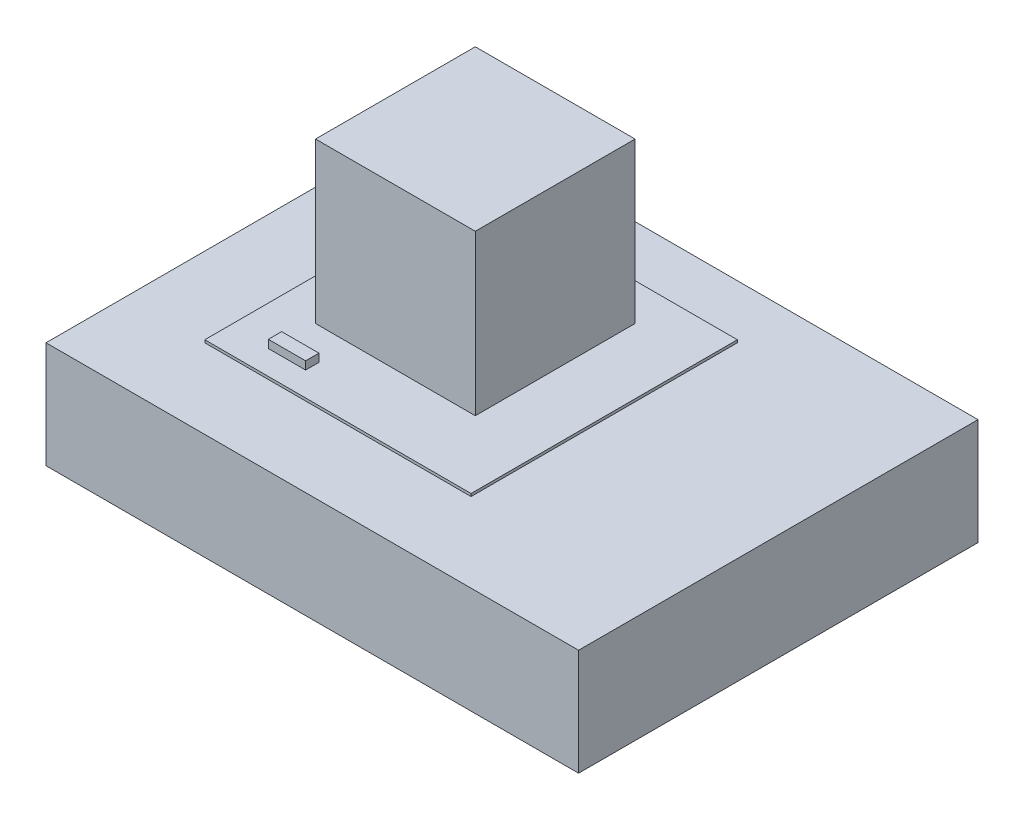
SolidWorks part; units mm, degrees
ref_plane "Спереди" through (0, 0, 0) normal (0, 0, 1) x (1, 0, 0)
ref_plane "Сверху" through (0, 0, 0) normal (0, 1, 0) x (1, 0, 0)
ref_plane "Справа" through (0, 0, 0) normal (1, 0, 0) x (0, 0, -1)
sketch "Эскиз10" plane through (0, 0, 0) normal (0, 1, 0) x (1, 0, 0)
  line L1 (-49.6102, 34.1278) -> (150.3898, 34.1278)
  line L2 (-49.6102, 34.1278) -> (-49.6102, -115.8722)
  line L3 (-49.6102, -115.8722) -> (150.3898, -115.8722)
  line L4 (150.3898, 34.1278) -> (150.3898, -115.8722)
  dimension "D1" = 200
  dimension "D2" = 150
extrude "подставка" add sketch "Эскиз10" along normal blind 40
sketch "Эскиз11" plane through (0, 40, 0) normal (0, 1, 0) x (1, 0, 0)
  line L1 (-19.7768, 13.9236) -> (80.2232, 13.9236)
  line L2 (-19.7768, 13.9236) -> (-19.7768, -86.0764)
  line L3 (-19.7768, -86.0764) -> (80.2232, -86.0764)
  line L4 (80.2232, 13.9236) -> (80.2232, -86.0764)
  dimension "D1" = 100
  dimension "D2" = 100
extrude "плата" add sketch "Эскиз11" along normal blind 1
sketch "Эскиз12" plane through (0, 41, 0) normal (0, 1, 0) x (1, 0, 0)
  line L1 (-4.2652, 0) -> (55.7348, 0)
  line L2 (-4.2652, 0) -> (-4.2652, -60)
  line L3 (-4.2652, -60) -> (55.7348, -60)
  line L4 (55.7348, 0) -> (55.7348, -60)
  dimension "D1" = 60
  dimension "D2" = 60
extrude "светодиоды" add sketch "Эскиз12" along normal blind 60
sketch "Эскиз13" plane through (0, 41, 0) normal (0, 1, 0) x (1, 0, 0)
  line L1 (-4.9877, -72.0001) -> (9.0123, -72.0001)
  line L2 (-4.9877, -72.0001) -> (-4.9877, -77.0001)
  line L3 (-4.9877, -77.0001) -> (9.0123, -77.0001)
  line L4 (9.0123, -72.0001) -> (9.0123, -77.0001)
  dimension "D1" = 14
  dimension "D2" = 5
extrude "микросхема" add sketch "Эскиз13" along normal blind 3
